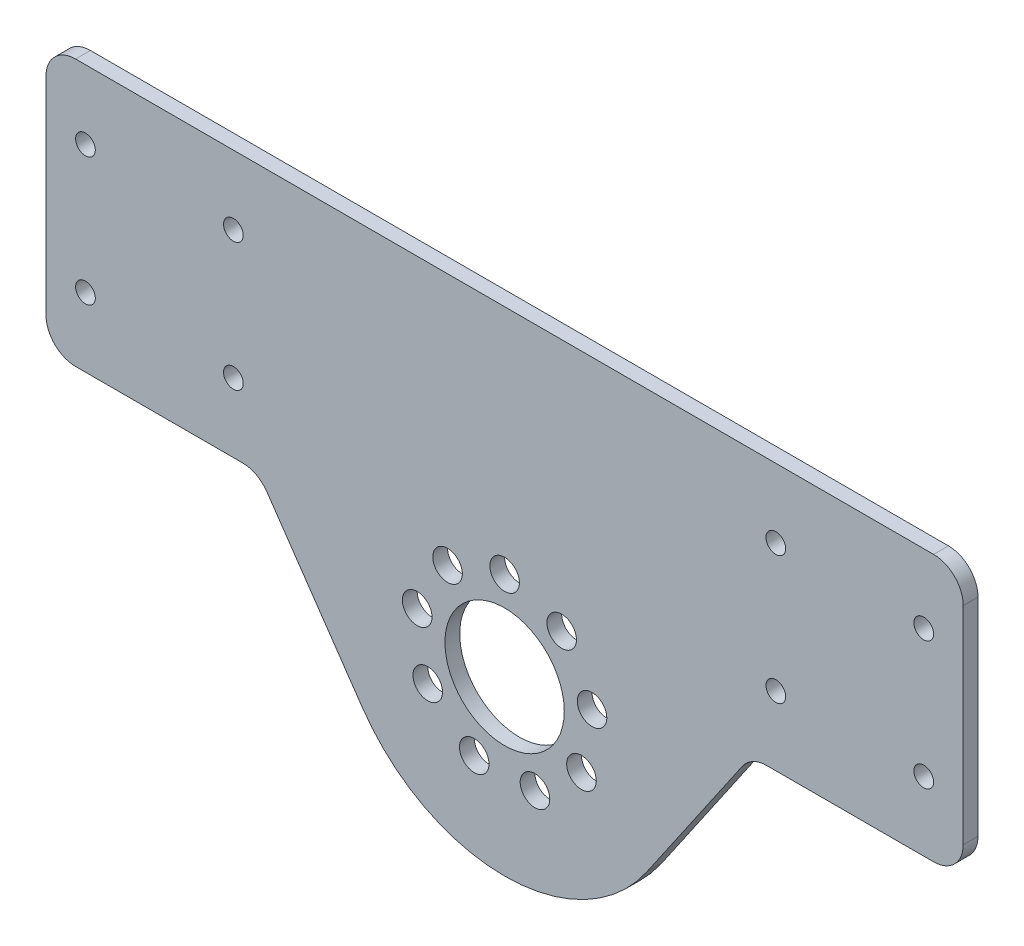
SolidWorks part; units mm, degrees
material "3.0205 (EN-AW 1200)"
ref_plane "Plan de face" through (0, 0, 0) normal (0, 0, 1) x (1, 0, 0)
ref_plane "Plan de dessus" through (0, 0, 0) normal (0, 1, 0) x (1, 0, 0)
ref_plane "Plan de droite" through (0, 0, 0) normal (1, 0, 0) x (0, 0, -1)
sketch "Esquisse1" plane through (0, 0, 0) normal (0, 0, 1) x (1, 0, 0)
  line L0 (0, 0) -> (0, -27) construction
  line L1 (-46.5, 0) -> (46.5, 0)
  line L2 (-46.5, 0) -> (-46.5, -27)
  line L3 (-46.5, -27) -> (46.5, -27)
  line L4 (46.5, 0) -> (46.5, -27)
  line L6 (35, -7) -> (42.5, -7) construction
  line L7 (35, -7) -> (35, -13.5) construction
  line L8 (35, -13.5) -> (42.5, -13.5) construction
  line L9 (42.5, -7) -> (42.5, -13.5) construction
  circle A0 centre (42.5, -7) radius 1
  circle A1 centre (27.5, -7) radius 1
  circle A2 centre (42.5, -20) radius 1
  circle A3 centre (27.5, -20) radius 1
  circle A4 centre (-42.5, -7) radius 1
  circle A5 centre (-42.5, -20) radius 1
  circle A6 centre (-27.5, -20) radius 1
  circle A7 centre (-27.5, -7) radius 1
  dimension "D1" = 15
  dimension "D2" = 13
  dimension "D3" = 2
  dimension "D4" = 4
  dimension "D5" = 7
  dimension "D6" = 70
  dimension "D8" = 7
  dimension "D7" = 93
extrude "Boss.-Extru.1" add sketch "Esquisse1" along normal blind 1.5
sketch "Esquisse2" plane through (0, 0, 1.5) normal (0, 0, 1) x (1, 0, 0)
  line L0 (-14.4286, -42.4028) -> (-25, -27)
  line L1 (14.4286, -42.4028) -> (25, -27)
  line L2 (-25, -27) -> (25, -27)
  line L3 (-46.5, -27) -> (46.5, -27) construction
  line L4 (46.5, 0) -> (-46.5, 0) construction
  arc A0 (-14.4286, -42.4028) -> (14.4286, -42.4028) centre (0, -32.5) ccw
  circle A1 centre (27.5, -20) radius 1 construction
  point P1 (0, -27)
  dimension "D1" = 12.5
  dimension "D2" = 17.5
  dimension "D4" = 50
  dimension "D3" = 50
extrude "Boss.-Extru.2" add sketch "Esquisse2" against normal up to surface (1.5 mm away) up to face at (-28.5, -20, 0)
sketch "Esquisse3" plane through (0, 0, 1.5) normal (0, 0, 1) x (1, 0, 0)
  circle A0 centre (0, -32.5) radius 6.05
  circle A1 centre (0, -23.5) radius 1.5
  arc A2 (-14.4286, -42.4028) -> (14.4286, -42.4028) centre (0, -32.5) ccw construction
  circle A3 centre (0, -32.5) radius 9 construction
  circle A4 centre (5.7851, -25.6056) radius 1.5
  circle A5 centre (8.8633, -30.9372) radius 1.5
  circle A6 centre (7.7942, -37) radius 1.5
  circle A7 centre (3.0782, -40.9572) radius 1.5
  circle A8 centre (-3.0782, -40.9572) radius 1.5
  circle A9 centre (-7.7942, -37) radius 1.5
  circle A10 centre (-8.8633, -30.9372) radius 1.5
  circle A11 centre (-5.7851, -25.6056) radius 1.5
  point P27 (0, -32.5)
  dimension "D1" = 3
  dimension "D2" = 18
  dimension "D3" = 12.1
  dimension "D4" = 9
extrude "Enlèv. mat.-Extru.1" cut sketch "Esquisse3" against normal through all
fillet "Congé2" radius 3 6 edges at (46.5, 0, 0.75) (46.5, -27, 0.75) (-46.5, -27, 0.75) (-46.5, 0, 0.75)
